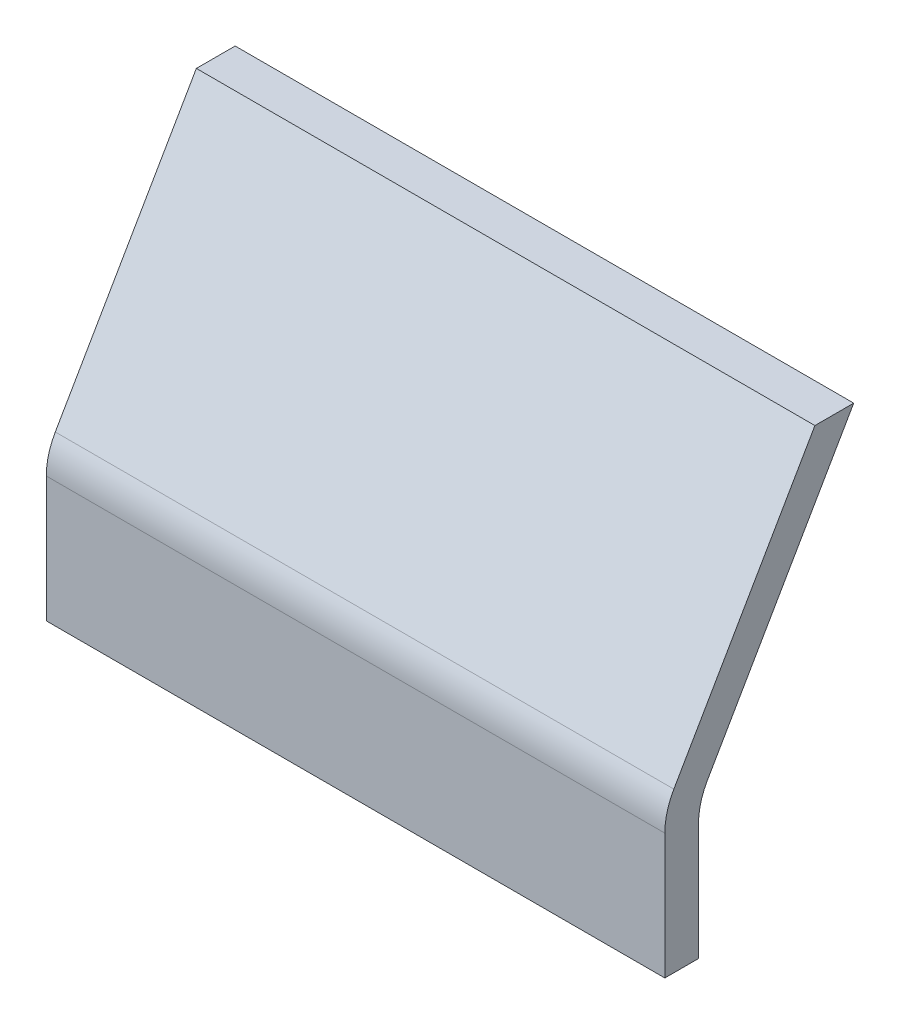
SolidWorks part; units mm, degrees
ref_plane "Front" through (0, 0, 0) normal (0, 0, 1) x (1, 0, 0)
ref_plane "Top" through (0, 0, 0) normal (0, 1, 0) x (1, 0, 0)
ref_plane "Right" through (0, 0, 0) normal (1, 0, 0) x (0, 0, -1)
sketch "Sketch1" plane through (0, 0, 0) normal (1, 0, 0) x (0, 0, -1)
  line L0 (0, 0) -> (0, 21.3397)
  line L1 (0, 21.3397) -> (22.3205, 60)
  line L2 (22.3205, 60) -> (28.094, 60)
  line L3 (28.094, 60) -> (5, 20)
  line L4 (5, 20) -> (5, 0)
  line L5 (5, 0) -> (0, 0)
  point P7 (25.2073, 60)
  dimension "D1" = 5
  dimension "D2" = 5
  dimension "D3" = 150
  dimension "D4" = 40
  dimension "D5" = 20
extrude "Boss-Extrude1" add sketch "Sketch1" along normal blind 92
fillet "Fillet1" radius 10 1 edges at (46, 21.3397, 0)
fillet "Fillet2" radius 10 1 edges at (46, 20, -5)
